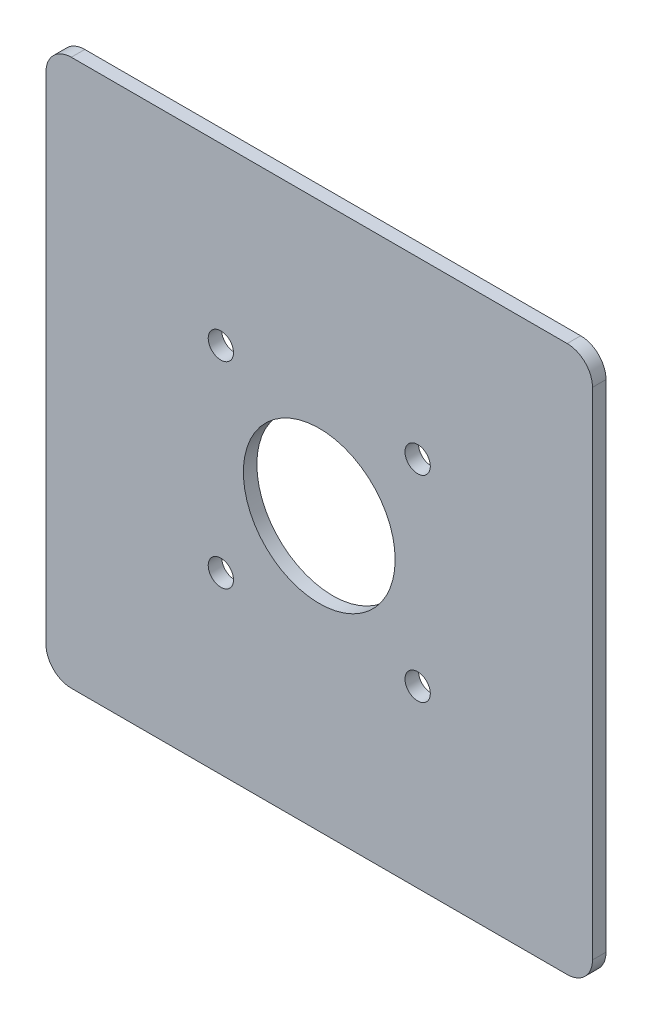
SolidWorks part; units mm, degrees
material "Plain Carbon Steel"
ref_plane "Front Plane" through (0, 0, 0) normal (0, 0, 1) x (1, 0, 0)
ref_plane "Top Plane" through (0, 0, 0) normal (0, 1, 0) x (1, 0, 0)
ref_plane "Right Plane" through (0, 0, 0) normal (1, 0, 0) x (0, 0, -1)
sketch "Sketch1" plane through (0, 0, 0) normal (0, 0, 1) x (1, 0, 0)
  line L1 (-162, -162) -> (162, -162)
  line L2 (-162, -162) -> (-162, 162)
  line L3 (-162, 162) -> (162, 162)
  line L4 (162, -162) -> (162, 162)
  line L5 (-162, -162) -> (162, 162) construction
  line L6 (-162, 162) -> (162, -162) construction
  point P0 (0, 0)
  dimension "D1" = 324
extrude "Boss-Extrude1" add sketch "Sketch1" along normal blind 8
sketch "Sketch2" plane through (0, 0, 8) normal (0, 0, 1) x (1, 0, 0)
  line L1 (-58.3363, -58.3363) -> (58.3363, -58.3363) construction
  line L2 (-58.3363, -58.3363) -> (-58.3363, 58.3363) construction
  line L3 (-58.3363, 58.3363) -> (58.3363, 58.3363) construction
  line L4 (58.3363, -58.3363) -> (58.3363, 58.3363) construction
  line L5 (-58.3363, -58.3363) -> (58.3363, 58.3363) construction
  line L6 (-58.3363, 58.3363) -> (58.3363, -58.3363) construction
  circle A1 centre (58.3363, 58.3363) radius 7.5
  circle A2 centre (0, 0) radius 82.5 construction
  point P0 (0, 0)
  dimension "D1" = 165
  dimension "D2" = 15
extrude "Cut-Extrude1" cut sketch "Sketch2" against normal blind 8
sketch "Sketch3" plane through (0, 0, 8) normal (0, 0, 1) x (1, 0, 0)
  circle A0 centre (0, 0) radius 45
  dimension "D1" = 90
extrude "Cut-Extrude2" cut sketch "Sketch3" against normal blind 10
pattern_circular "CirPattern1" count 4 over 360 about axis through (0, 0, 0) along (0, 0, 1) of "Cut-Extrude1"
fillet "Fillet1" radius 15 4 edges at (162, -162, 4) (162, 162, 4) (-162, 162, 4) (-162, -162, 4)
